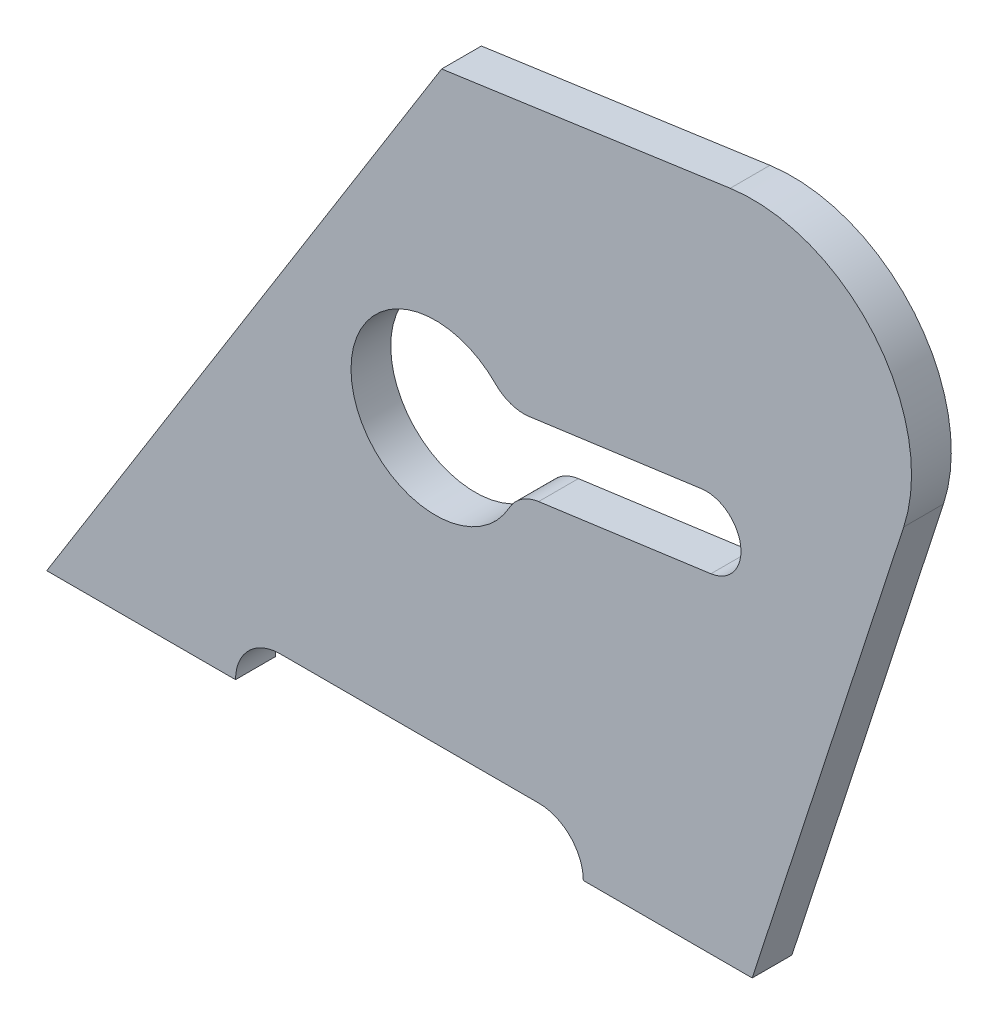
SolidWorks part; units mm, degrees
ref_plane "Front Plane" through (0, 0, 0) normal (0, 0, 1) x (1, 0, 0)
ref_plane "Top Plane" through (0, 0, 0) normal (0, 1, 0) x (1, 0, 0)
ref_plane "Right Plane" through (0, 0, 0) normal (1, 0, 0) x (0, 0, -1)
sketch "Sketch1" plane through (0, 0, 0) normal (0, 0, 1) x (1, 0, 0)
  line L0 (0, 0) -> (79.4879, 127.2072)
  line L1 (79.4879, 127.2072) -> (137.573, 135.4513)
  line L2 (172.5035, 93.8803) -> (142, 0)
  line L3 (142, 0) -> (108, 0)
  line L4 (99, 9) -> (47, 9)
  line L5 (38, 0) -> (0, 0)
  line L6 (79.4879, 127.2072) -> (188.3525, 142.6585) construction
  line L7 (142, 0) -> (188.3525, 142.6585) construction
  line L8 (37.6243, 60.2114) -> (167.3394, 77.9866) construction
  line L9 (97.1091, 75.4282) -> (131.7851, 80.1799)
  line L10 (99.0098, 61.5578) -> (133.6858, 66.3096)
  line L11 (132.7354, 73.2448) -> (131.7851, 80.1799) construction
  line L12 (132.7354, 73.2448) -> (133.6858, 66.3096) construction
  arc A0 (137.573, 135.4513) -> (172.5035, 93.8803) centre (142.0697, 103.7688) cw
  arc A1 (108, 0) -> (99, 9) centre (99, 0) ccw
  arc A2 (47, 9) -> (38, 0) centre (47, 0) ccw
  arc A3 (90.3339, 77.7297) -> (93.1035, 57.5186) centre (78.2447, 65.7777) ccw
  arc A6 (133.6858, 66.3096) -> (131.7851, 80.1799) centre (132.7354, 73.2448) ccw
  arc A7 (97.1091, 75.4282) -> (90.3339, 77.7297) centre (96.023, 83.3541) cw
  arc A8 (99.0098, 61.5578) -> (93.1035, 57.5186) centre (100.0959, 53.6319) ccw
  dimension "D3" = 32
  dimension "D11" = 0
  dimension "D14" = 0
  dimension "D15" = 14
  dimension "D19" = 8
  dimension "D20" = 8
  dimension "D21" = 34
  dimension "D1" = 58
  dimension "D2" = 108
  dimension "D4" = 0
  dimension "D5" = 150
  dimension "D6" = 150
  dimension "D7" = 52
  dimension "D8" = 47
  dimension "D9" = 9
  dimension "D10" = 0
  dimension "D12" = 71
  dimension "D13" = 82
  dimension "D16" = 55
  dimension "D17" = 41
  dimension "D18" = 142
extrude "Boss-Extrude1" add sketch "Sketch1" along normal blind 8
